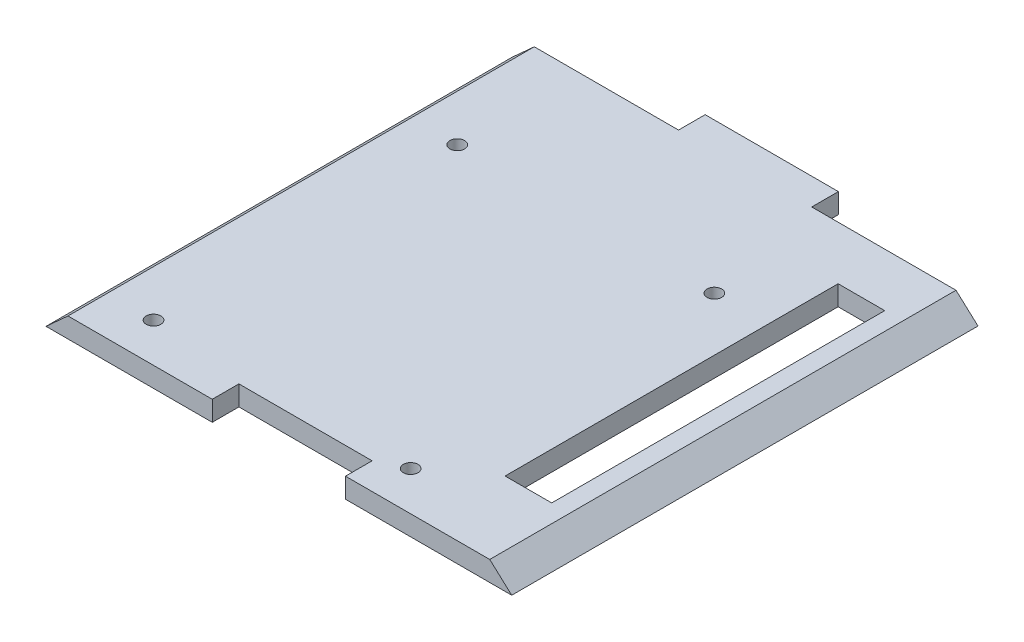
SolidWorks part; units mm, degrees
ref_plane "Front Plane" through (0, 0, 0) normal (0, 0, 1) x (1, 0, 0)
ref_plane "Top Plane" through (0, 0, 0) normal (0, 1, 0) x (1, 0, 0)
ref_plane "Right Plane" through (0, 0, 0) normal (1, 0, 0) x (0, 0, -1)
sketch "Sketch1" plane through (0, 0, 0) normal (0, 0, 1) x (1, 0, 0)
  line L0 (0, 0) -> (0, 44.45) construction
  line L1 (-40.2039, 5.9378) -> (40.2039, 5.9378)
  line L2 (-44.399, 2.1278) -> (44.399, 2.1278)
  line L3 (-40.2039, 5.9378) -> (-44.399, 2.1278)
  line L4 (40.2039, 5.9378) -> (44.399, 2.1278)
  arc A0 (44.399, 2.1278) -> (-44.399, 2.1278) centre (0, 0) ccw construction
  arc A1 (40.2039, 5.9378) -> (-40.2039, 5.9378) centre (0, 0) ccw construction
  dimension "D1" = 88.9
  dimension "D2" = 3.81
  dimension "D3" = 3.81
extrude "Boss-Extrude1" add sketch "Sketch1" along normal blind 88.9
sketch "Sketch2" plane through (0, 2.1278, 0) normal (0, -1, 0) x (1, 0, 0)
  line L0 (0, 88.9) -> (0, 0) construction
  line L1 (-34.417, 85.09) -> (20.701, 85.09) construction
  line L2 (-34.417, 85.09) -> (-34.417, 0) construction
  line L3 (-34.417, 0) -> (20.701, 0) construction
  line L4 (20.701, 85.09) -> (20.701, 0) construction
  line L5 (-44.399, 88.9) -> (44.399, 88.9) construction
  line L6 (-44.399, 0) -> (44.399, 0) construction
  line L7 (-34.417, 42.545) -> (20.701, 42.545) construction
  line L8 (-6.858, 85.09) -> (-6.858, 0) construction
  circle A0 centre (-31.369, 81.43) radius 1.397
  circle A1 centre (17.653, 23.518) radius 1.397
  circle A2 centre (-31.369, 23.518) radius 1.397
  circle A3 centre (17.653, 81.43) radius 1.397
  point P10 (-6.858, 85.09)
  dimension "D4" = 2.794
  dimension "D7" = 2.794
  dimension "D8" = 57.912
  dimension "D5" = 49.022
  dimension "D1" = 6.858
  dimension "D2" = 85.09
  dimension "D3" = 3.81
  dimension "D6" = 55.118
extrude "Cut-Extrude1" cut sketch "Sketch2" against normal through all
sketch "Sketch3" plane through (0, 2.1278, 0) normal (0, -1, 0) x (1, 0, 0)
  line L0 (0, 88.9) -> (0, 0) construction
  line L1 (-44.399, 88.9) -> (44.399, 88.9) construction
  line L2 (-44.399, 0) -> (44.399, 0) construction
  line L3 (0, 44.45) -> (44.399, 44.45) construction
  line L4 (-12.7, 88.9) -> (12.7, 88.9)
  line L5 (-12.7, 88.9) -> (-12.7, 83.82)
  line L6 (-12.7, 83.82) -> (12.7, 83.82)
  line L7 (12.7, 88.9) -> (12.7, 83.82)
  line L8 (44.399, 88.9) -> (44.399, 0) construction
  line L9 (0, 44.45) -> (-44.399, 44.45) construction
  line L10 (-44.399, 88.9) -> (-44.399, 0) construction
  line L11 (12.7, 0) -> (12.7, 5.08)
  line L12 (-12.7, 5.08) -> (12.7, 5.08)
  line L13 (-12.7, 0) -> (12.7, 0)
  line L14 (-12.7, 0) -> (-12.7, 5.08)
  point P10 (12.7, 86.36)
  dimension "D1" = 25.4
  dimension "D2" = 12.7
  dimension "D3" = 5.08
extrude "Cut-Extrude2" cut sketch "Sketch3" against normal through all
sketch "Sketch5" plane through (0, 2.1278, 0) normal (0, -1, 0) x (1, 0, 0)
  line L0 (12.7, 0) -> (12.7, 5.08) construction
  line L1 (12.7, 5.08) -> (-12.7, 5.08)
  line L2 (12.7, 5.08) -> (12.7, -5.08)
  line L3 (12.7, -5.08) -> (-12.7, -5.08)
  line L4 (-12.7, 5.08) -> (-12.7, -5.08)
  line L5 (12.7, 5.08) -> (-12.7, 5.08) construction
  dimension "D1" = 0
  dimension "D2" = 25.4
  dimension "D3" = 10.16
extrude "Boss-Extrude3" add sketch "Sketch5" against normal blind 3.81
sketch "Sketch6" plane through (0, 2.1278, 0) normal (0, -1, 0) x (1, 0, 0)
  line L0 (12.7, 88.9) -> (44.399, 88.9) construction
  line L1 (27.889, 73.66) -> (36.779, 73.66)
  line L2 (27.889, 73.66) -> (27.889, 10.16)
  line L3 (27.889, 10.16) -> (36.779, 10.16)
  line L4 (36.779, 73.66) -> (36.779, 10.16)
  line L5 (44.399, 88.9) -> (44.399, 0) construction
  dimension "D1" = 15.24
  dimension "D2" = 7.62
  dimension "D3" = 63.5
  dimension "D4" = 8.89
extrude "Cut-Extrude3" cut sketch "Sketch6" against normal through all
